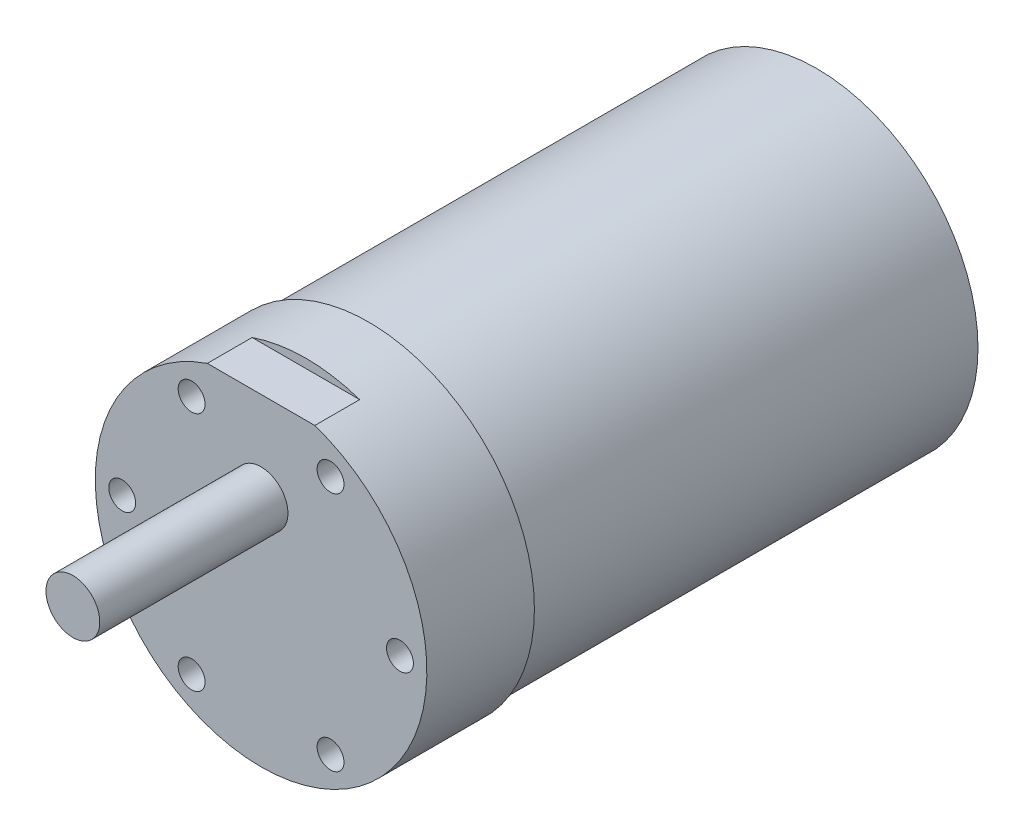
SolidWorks part; units mm, degrees
ref_plane "Front Plane" through (0, 0, 0) normal (0, 0, 1) x (1, 0, 0)
ref_plane "Top Plane" through (0, 0, 0) normal (0, 1, 0) x (1, 0, 0)
ref_plane "Right Plane" through (0, 0, 0) normal (1, 0, 0) x (0, 0, -1)
sketch "Sketch1" plane through (0, 0, 0) normal (0, 0, 1) x (1, 0, 0)
  line L0 (6.1021, 51.3432) -> (6.1021, 40.3432) construction
  circle A0 centre (6.1021, 32.8432) radius 15.5 construction
  circle A1 centre (21.6021, 32.8432) radius 1.5
  circle A2 centre (13.8521, 19.4198) radius 1.5
  circle A3 centre (-1.6479, 19.4198) radius 1.5
  circle A4 centre (-9.3979, 32.8432) radius 1.5
  circle A5 centre (-1.6479, 46.2666) radius 1.5
  circle A6 centre (13.8521, 46.2666) radius 1.5
  circle A7 centre (6.1021, 32.8432) radius 18.5
  circle A8 centre (6.1021, 40.3432) radius 6.1
  point P16 (6.1021, 32.8432)
  dimension "D1" = 6
extrude "Boss-Extrude1" add sketch "Sketch1" along normal blind 12
sketch "Sketch2" plane through (0, 0, 0) normal (0, 0, -1) x (-1, 0, 0)
  circle A0 centre (-6.1021, 32.8432) radius 18
extrude "Boss-Extrude2" add sketch "Sketch2" along normal blind 50
sketch "Sketch3" plane through (0, 0, 12) normal (0, 0, 1) x (1, 0, 0)
  circle A0 centre (6.1021, 40.3432) radius 3
extrude "Boss-Extrude3" add sketch "Sketch3" along normal blind 21 separate body
sketch "Sketch4" plane through (0, 0, 0) normal (0, 0, 1) x (1, 0, 0)
  circle A1 centre (6.1021, 40.3432) radius 6.1
  circle A2 centre (6.1021, 40.3432) radius 6.1
  dimension "D1" = 0
extrude "Boss-Extrude4" add sketch "Sketch4" along normal up to surface (12 mm away) up to face at (15.3521, 46.2666, 12)
sketch "Sketch5" plane through (0, 0, 12) normal (0, 0, 1) x (1, 0, 0)
  line L0 (6.1021, 51.3432) -> (6.1021, 50.3432)
  line L1 (6.1021, 50.3432) -> (13.8645, 50.3432)
  line L2 (13.8645, 50.3432) -> (13.8645, 52.3257)
  line L3 (13.8645, 52.3257) -> (-3.18, 52.3257)
  line L4 (-3.18, 52.3257) -> (-3.18, 50.3432)
  line L5 (-3.18, 50.3432) -> (6.1021, 50.3432)
  circle A0 centre (6.1021, 32.8432) radius 18.5 construction
  circle M5 centre (6.1021, 32.8432) radius 18.5
extrude "Cut-Extrude1" cut sketch "Sketch5" against normal blind 5 contours L5 L0 M5 | L0 L1 M5
scale "Scale1" scale about centroid uniform scaling yes scale factor 0.8
scale "Scale2" scale about centroid uniform scaling yes scale factor 1
scale "Scale3" scale about centroid uniform scaling yes scale factor 1.1
